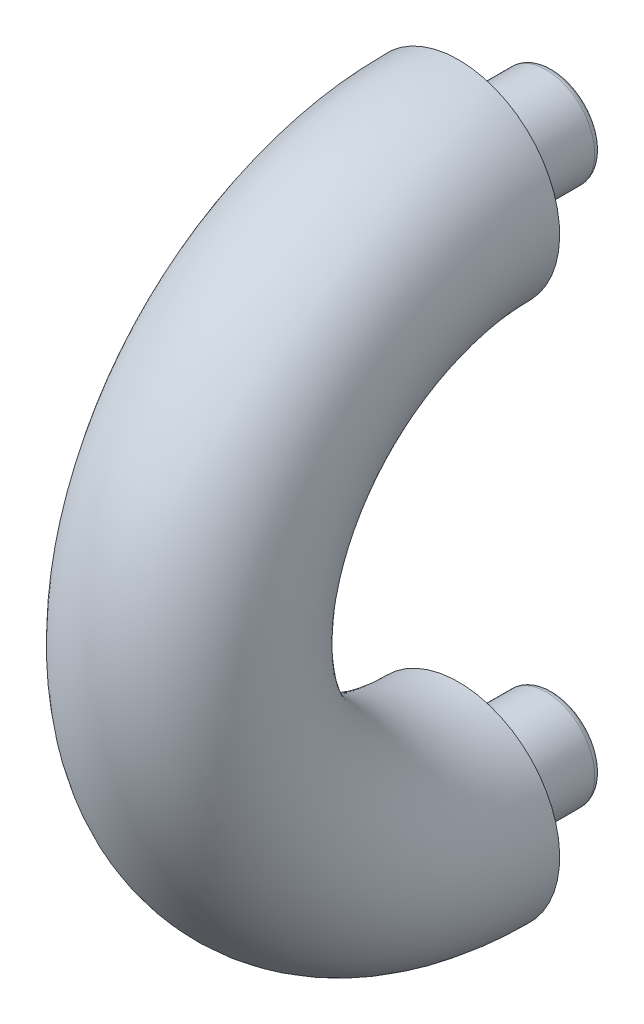
SolidWorks part; units mm, degrees
ref_plane "Front Plane" through (0, 0, 0) normal (1, 0, 0) x (0, 1, 0)
ref_plane "Top Plane" through (0, 0, 0) normal (0, 0, 1) x (0, 1, 0)
ref_plane "Right Plane" through (0, 0, 0) normal (0, 1, 0) x (-1, 0, 0)
sketch "Sketch1" plane through (0, 0, 0) normal (1, 0, 0) x (0, 1, 0)
  circle A0 centre (0, 0) radius 50.8
  dimension "D1" = 101.6
sweep "Sweep1" add path "Sketch1" circular profile diameter 38.1 parameters "D3"=38.1
sketch "Sketch8" plane through (0, 0, 0) normal (1, 0, 0) x (0, 1, 0)
  line L0 (83.0145, 0) -> (-95.8864, 0)
  line L1 (-95.8864, -78.0709) -> (83.0145, -78.0709)
  line L2 (83.0145, -78.0709) -> (83.0145, 0)
  line L3 (-95.8864, 0) -> (-95.8864, -78.0709)
extrude "Cut-Extrude1" cut sketch "Sketch8" against normal blind 73.406 and the other way blind 63.5
sketch "Sketch9" plane through (0, 0, 0) normal (0, 0, -1) x (1, 0, 0)
  line L0 (0, 75.2727) -> (0, -76.9516) construction
  line L1 (-19.05, 50.8) -> (19.05, 50.8) construction
  line L2 (-19.05, -50.8) -> (19.05, -50.8) construction
  circle A0 centre (0, 50.8) radius 9.144
  circle A1 centre (0, -50.8) radius 9.144
  dimension "D1" = 18.288
  dimension "D2" = 18.288
extrude "Boss-Extrude1" add sketch "Sketch9" along normal blind 17.78
fillet "Fillet1" radius 1.27 2 edges at (-9.144, -50.8, -17.78) (-9.144, 50.8, -17.78)
fillet "Fillet2" radius 1.27 2 edges at (-9.144, 50.8, 0) (-9.144, -50.8, 0)
